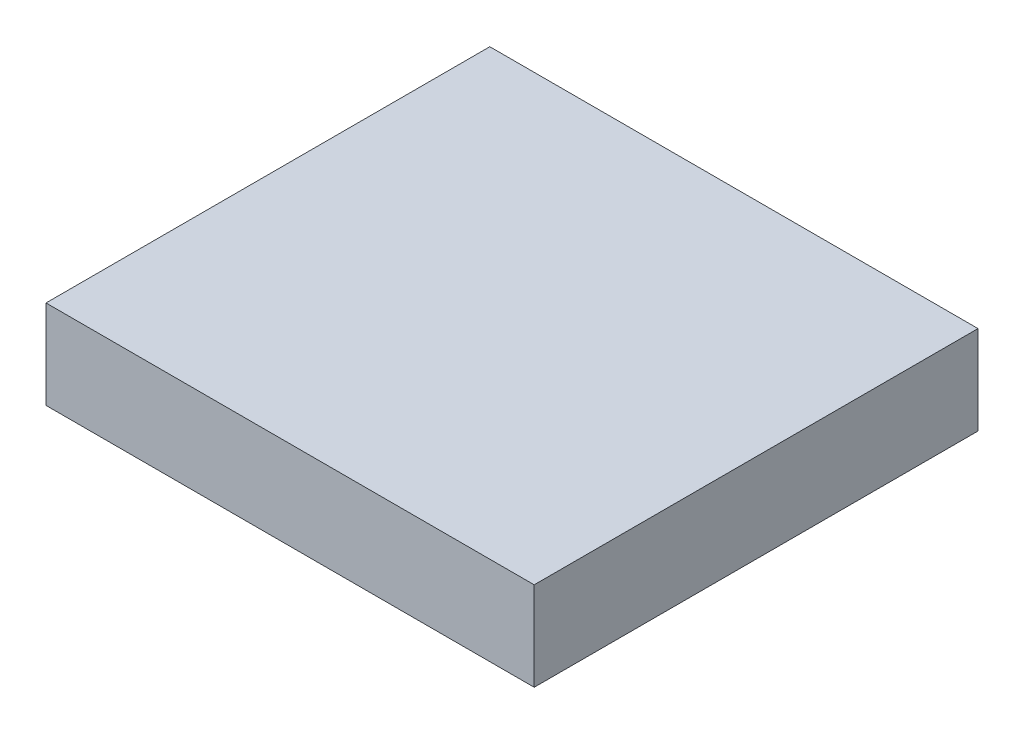
SolidWorks part; units mm, degrees
ref_plane "Front Plane" through (0, 0, 0) normal (0, 0, 1) x (1, 0, 0)
ref_plane "Top Plane" through (0, 0, 0) normal (0, 1, 0) x (1, 0, 0)
ref_plane "Right Plane" through (0, 0, 0) normal (1, 0, 0) x (0, 0, -1)
sketch "Sketch1" plane through (0, 0, 0) normal (0, 1, 0) x (1, 0, 0)
  line L1 (-5.5, 5) -> (5.5, 5)
  line L2 (-5.5, 5) -> (-5.5, -5)
  line L3 (-5.5, -5) -> (5.5, -5)
  line L4 (5.5, 5) -> (5.5, -5)
  line L5 (-5.5, 5) -> (5.5, -5) construction
  line L6 (-5.5, -5) -> (5.5, 5) construction
  point P0 (0, 0)
  dimension "D1" = 10
  dimension "D2" = 11
extrude "Boss-Extrude1" add sketch "Sketch1" along normal blind 2
